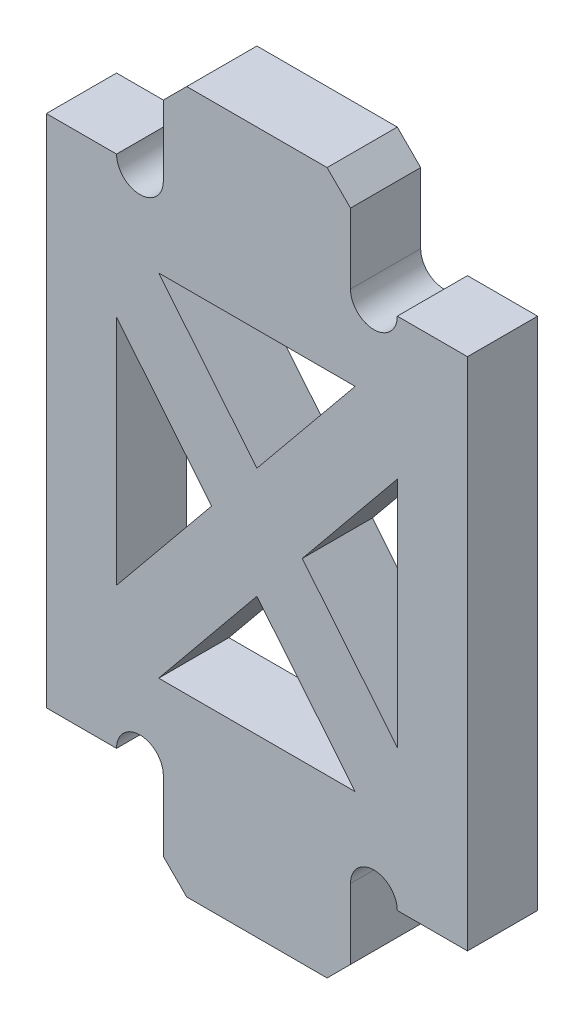
SolidWorks part; units mm, degrees
material "碳板"
ref_plane "前视基准面" through (0, 0, 0) normal (0, 0, 1) x (1, 0, 0)
ref_plane "上视基准面" through (0, 0, 0) normal (0, 1, 0) x (1, 0, 0)
ref_plane "右视基准面" through (0, 0, 0) normal (1, 0, 0) x (0, 0, -1)
sketch "草图1" plane through (0, 0, 0) normal (0, 0, 1) x (1, 0, 0)
  line L0 (0, 19.9183) -> (0, -17.9901) construction
  line L1 (-9, 11) -> (9, 11)
  line L2 (-9, 11) -> (-9, -11)
  line L3 (-9, -11) -> (9, -11)
  line L4 (9, 11) -> (9, -11)
  line L5 (-9, 11) -> (9, -11) construction
  line L6 (-9, -11) -> (9, 11) construction
  line L7 (-22.5399, 0) -> (24.3637, 0) construction
  line L8 (-4, 11) -> (-4, 15)
  line L9 (-4, 15) -> (4, 15)
  line L10 (4, 11) -> (4, 15)
  line L11 (4, -11) -> (4, -15)
  line L12 (-4, -15) -> (4, -15)
  line L13 (-4, -11) -> (-4, -15)
  line L14 (4.1983, 7.5) -> (-4.1983, 7.5)
  line L15 (-4.1983, 7.5) -> (0, 2.3688)
  line L16 (-1.9381, 0) -> (-6, 4.9646)
  line L17 (-6, 4.9646) -> (-6, -4.9646)
  line L18 (4.1983, 7.5) -> (0, 2.3688)
  line L19 (1.9381, 0) -> (6, 4.9646)
  line L20 (6, 4.9646) -> (6, -4.9646)
  line L21 (1.9381, 0) -> (6, -4.9646)
  line L22 (4.1983, -7.5) -> (-4.1983, -7.5)
  line L23 (-4.1983, -7.5) -> (0, -2.3688)
  line L24 (4.1983, -7.5) -> (0, -2.3688)
  line L25 (-1.9381, 0) -> (-6, -4.9646)
  circle A0 centre (-5, 11) radius 1
  circle A1 centre (5, 11) radius 1
  circle A2 centre (5, -11) radius 1
  circle A3 centre (-5, -11) radius 1
  point P0 (0, 0)
  point P15 (0, 15)
  point P34 (0, 7.5)
  point P38 (6, 0)
  point P42 (-6, 0)
  dimension "D4" = 2
  dimension "D1" = 30
  dimension "D2" = 4
  dimension "D3" = 8
  dimension "D5" = 4
  dimension "D6" = 1.5
  dimension "D7" = 1.5
  dimension "D8" = 3
  dimension "D9" = 3.5
extrude "凸台-拉伸1" add sketch "草图1" along normal mid plane 3 contours L3 A3 A2 L4 L1 A1 A0 L2 L24 L22 L23 L21 L19 L20 L14 L18 L15 L16 L25 L17 | L1 L10 L9 L8 | L3 L13 L12 L11
chamfer "倒角1" distance 1 angle 45 4 edges at (4, -15, 0) (-4, -15, 0) (4, 15, 0) (-4, 15, 0)
